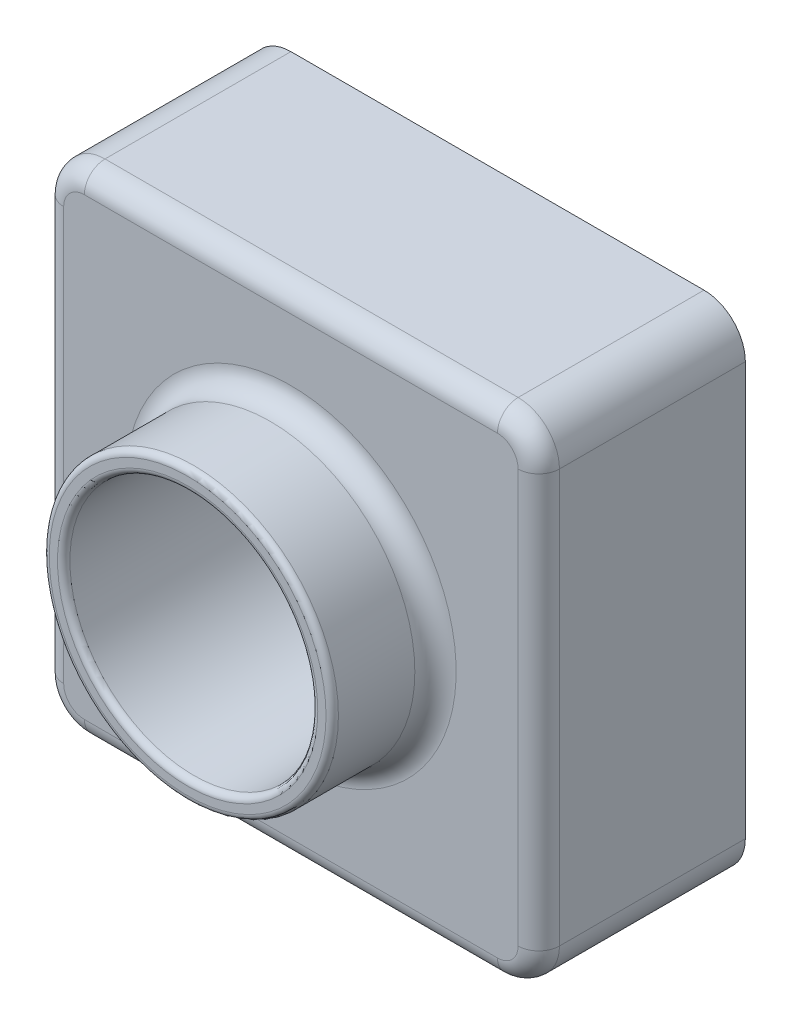
SolidWorks part; units mm, degrees
ref_plane "Alzado" through (0, 0, 0) normal (0, 0, 1) x (1, 0, 0)
ref_plane "Planta" through (0, 0, 0) normal (0, 1, 0) x (1, 0, 0)
ref_plane "Vista lateral" through (0, 0, 0) normal (1, 0, 0) x (0, 0, -1)
sketch "Croquis1" plane through (0, 0, 0) normal (0, 0, 1) x (1, 0, 0)
  line L1 (-50, -60) -> (50, -60)
  line L2 (-60, -50) -> (-60, 50)
  line L3 (-50, 60) -> (50, 60)
  line L4 (60, -50) -> (60, 50)
  line L5 (-60, -60) -> (60, 60) construction
  line L6 (-60, 60) -> (60, -60) construction
  arc A0 (-50, -60) -> (-60, -50) centre (-50, -50) cw
  arc A1 (50, -60) -> (60, -50) centre (50, -50) ccw
  arc A2 (50, 60) -> (60, 50) centre (50, 50) cw
  arc A3 (-60, 50) -> (-50, 60) centre (-50, 50) cw
  point P0 (0, 0)
  dimension "D3" = 10
  dimension "D1" = 120
  dimension "D2" = 120
extrude "Saliente-Extruir1" add sketch "Croquis1" along normal blind 50
sketch "Croquis2" plane through (0, 0, 50) normal (0, 0, 1) x (1, 0, 0)
  circle A0 centre (0, 0) radius 35
  circle A1 centre (0, 0) radius 30
  dimension "D1" = 70
  dimension "D2" = 60
shell "Vaciado2" thickness 2
extrude "Saliente-Extruir3" add sketch "Croquis2" along normal blind 25 and the other way blind 50
sketch "Croquis3" plane through (0, 0, 75) normal (0, 0, 1) x (1, 0, 0)
  circle A0 centre (0, 0) radius 30
extrude "Cortar-Extruir1" cut sketch "Croquis3" against normal through all
fillet "Redondeo1" radius 1.5 4 edges at (35, 0, 0) (30, 0, 0) (30, 0, 75) (35, 0, 75)
fillet "Redondeo2" radius 5 2 edges at (-35, 0, 48) (-35, 0, 50)
fillet "Redondeo3" radius 5 8 edges at (-60, 0, 50) (-57.0711, 57.0711, 50) (0, 60, 50) (57.0711, 57.0711, 50) (60, 0, 50) (57.0711, -57.0711, 50) (0, -60, 50) (-57.0711, -57.0711, 50)
sketch "Croquis4" plane through (0, 0, 50) normal (0, 0, 1) x (1, 0, 0)
  line L0 (-45.5184, 43.8414) -> (45.9976, 44.7997) construction
  text T0 "SOLIDWORKS 2026 " font "Century Gothic" height 5.5
